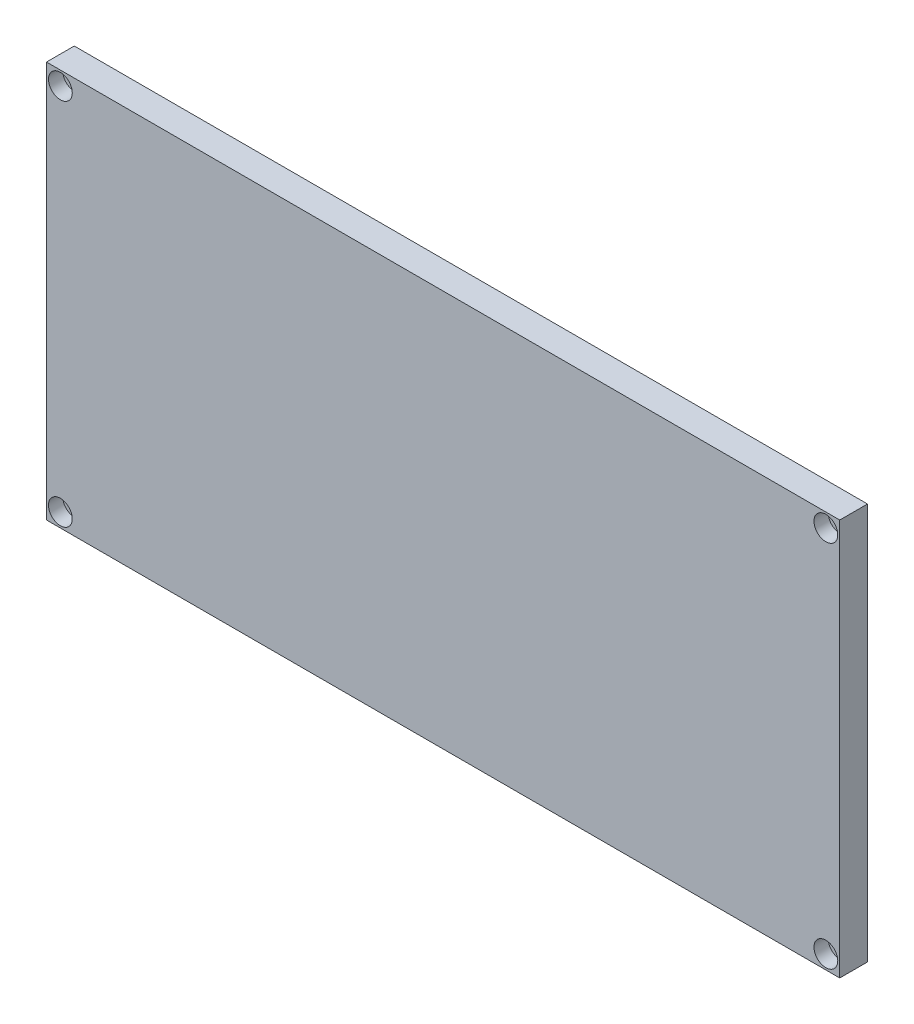
SolidWorks part; units mm, degrees
ref_plane "Front Plane" through (0, 0, 0) normal (0, 0, 1) x (1, 0, 0)
ref_plane "Top Plane" through (0, 0, 0) normal (0, 1, 0) x (1, 0, 0)
ref_plane "Right Plane" through (0, 0, 0) normal (1, 0, 0) x (0, 0, -1)
sketch "Sketch1" plane through (0, 0, 0) normal (0, 0, 1) x (1, 0, 0)
  line L1 (-25.4, 12.7) -> (25.4, 12.7)
  line L2 (-25.4, 12.7) -> (-25.4, -12.7)
  line L3 (-25.4, -12.7) -> (25.4, -12.7)
  line L4 (25.4, 12.7) -> (25.4, -12.7)
  dimension "D1" = 25.4
  dimension "D2" = 50.8
  dimension "D3" = 12.7
  dimension "D4" = 25.4
extrude "Boss-Extrude1" add sketch "Sketch1" against normal blind 1.778
sketch "Sketch2" plane through (0, 0, 0) normal (0, 0, 1) x (1, 0, 0)
  line L0 (0, 15.3811) -> (0, -16.9294) construction
  line L1 (28.7911, 0) -> (-28.0464, 0) construction
  line L2 (25.4, 12.7) -> (-25.4, 12.7) construction
  line L3 (-25.4, 12.7) -> (-25.4, -12.7) construction
  circle A0 centre (-24.511, 11.811) radius 0.762
  circle A1 centre (24.511, 11.811) radius 0.762
  circle A2 centre (24.511, -11.811) radius 0.762
  circle A3 centre (-24.511, -11.811) radius 0.762
  dimension "D1" = 1.524
  dimension "D2" = 0.889
  dimension "D3" = 0.889
extrude "Cut-Extrude2" cut sketch "Sketch2" against normal blind 0.9144
